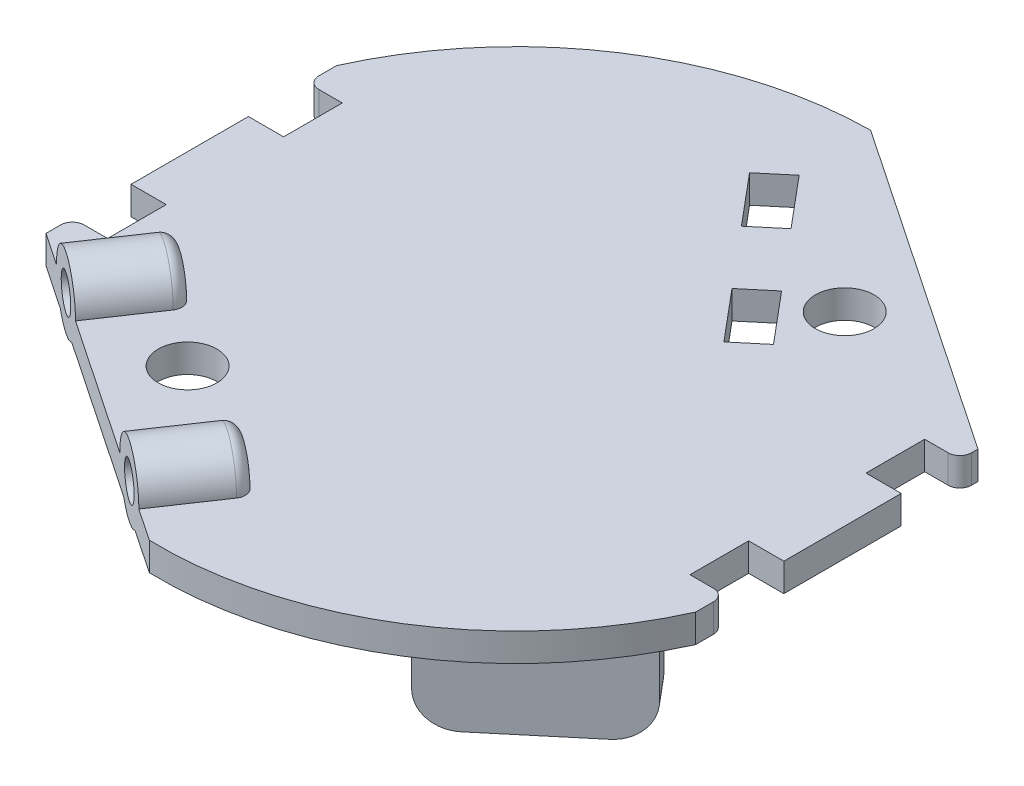
SolidWorks part; units mm, degrees
ref_plane "Alzado" through (0, 0, 0) normal (0, 0, 1) x (1, 0, 0)
ref_plane "Planta" through (0, 0, 0) normal (0, 1, 0) x (1, 0, 0)
ref_plane "Vista lateral" through (0, 0, 0) normal (1, 0, 0) x (0, 0, -1)
sketch "Croquis1" plane through (0, 0, 0) normal (0, 1, 0) x (1, 0, 0)
  circle A0 centre (0, 0) radius 30.5
extrude "Saliente-Extruir1" add sketch "Croquis1" along normal blind 2.4
sketch "Croquis5" plane through (0, 2.4, 0) normal (0, 1, 0) x (1, 0, 0)
  line L0 (0, 0) -> (0, 10)
  line L1 (28.8141, -5) -> (30.0874, -5)
  line L2 (28.8141, 5) -> (30.0874, 5)
  line L3 (-24.8141, 10) -> (-28.8141, 10)
  line L4 (24.8141, -5) -> (24.8141, -10)
  line L5 (-24.8141, -10) -> (-28.8141, -10)
  line L6 (24.8141, -5) -> (28.8141, -5)
  line L7 (24.8141, 5) -> (24.8141, 10)
  line L8 (-24.8141, 5) -> (-28.8141, 5)
  line L9 (-24.8141, 5) -> (-24.8141, 10)
  line L10 (-24.8141, -5) -> (-28.8141, -5)
  line L11 (-24.8141, -5) -> (-24.8141, -10)
  line L12 (24.8141, 5) -> (28.8141, 5)
  line L13 (24.8141, -10) -> (28.8141, -10)
  line L14 (24.8141, 10) -> (28.8141, 10)
  line L15 (-28.8141, 5) -> (-30.0874, 5)
  line L16 (-28.8141, -5) -> (-30.0874, -5)
  circle A1 centre (0, 0) radius 30.5 construction
  arc A2 (-28.8141, 10) -> (-30.0874, 5) centre (0, 0) ccw
  arc A3 (28.8141, 10) -> (28.8141, -10) centre (0, 0) cw
  arc A4 (-30.0874, -5) -> (-28.8141, -10) centre (0, 0) ccw
  arc A5 (30.0874, -5) -> (28.8141, -10) centre (0, 0) cw
  arc A6 (28.8141, 10) -> (30.0874, 5) centre (0, 0) cw
extrude "Cortar-Extruir3" cut sketch "Croquis5" against normal blind 4
sketch "Croquis9" plane through (0, 2.4, 0) normal (0, 1, 0) x (1, 0, 0)
  line L0 (5.6733, 12.6854) -> (8.8872, 8.8552)
  line L2 (7.9714, 14.6138) -> (11.1854, 10.7835)
  line L3 (-24.8141, -5) -> (-24.8141, -10)
  line L4 (-24.8141, -10) -> (-28.8141, -10)
  line L5 (11.1854, 10.7835) -> (8.8872, 8.8552)
  line L7 (7.9714, 14.6138) -> (5.6733, 12.6854)
  line L11 (-2.1205, 21.9737) -> (1.0934, 18.1435)
  line L12 (0.1776, 23.902) -> (3.3916, 20.0718)
  line L13 (-24.8141, 10) -> (-28.8141, 10)
  line L14 (3.3916, 20.0718) -> (1.0934, 18.1435)
  line L15 (0.1776, 23.902) -> (-2.1205, 21.9737)
  arc A1 (28.8141, 10) -> (-28.8141, 10) centre (0, 0) ccw construction
  arc A5 (-28.8141, -10) -> (28.8141, -10) centre (0, 0) ccw construction
  arc A7 (-28.8141, -10) -> (22.3289, -20.7766) centre (0, 0) ccw
  arc A8 (-28.8141, 10) -> (-8.3073, 29.3469) centre (0, 0) cw
extrude "Cortar-Extruir6" cut sketch "Croquis9" against normal blind 10
sketch "Croquis10" plane through (0, 2.4, 0) normal (0, 1, 0) x (1, 0, 0)
  line L0 (0, 0) -> (12, 0)
  line L1 (12, 0) -> (12, 16)
  line L2 (0, 0) -> (-12, 0)
  line L3 (-12, 0) -> (-12, -16)
  circle A0 centre (12, 16) radius 2.5
  circle A1 centre (-12, -16) radius 2.5
extrude "Cortar-Extruir7" cut sketch "Croquis10" against normal blind 10
sketch "Croquis11" plane through (0, 2.4, 0) normal (0, 1, 0) x (1, 0, 0)
  line L0 (27.8141, 5) -> (30.0874, 5)
  line L1 (-27.8141, 5) -> (-27.8141, -5)
  line L2 (-24.8141, -5) -> (-30.0874, -5) construction
  line L3 (27.8141, 10) -> (28.8141, 10)
  line L4 (24.8141, 5) -> (30.0874, 5) construction
  line L5 (27.8141, 5) -> (27.8141, -5)
  line L6 (24.8141, -5) -> (30.0874, -5) construction
  line L7 (27.8141, -5) -> (30.0874, -5)
  line L8 (24.8141, 10) -> (28.8141, 10) construction
  line L9 (27.8141, 10) -> (27.8141, 12.5151)
  line L10 (27.8141, -10) -> (28.8141, -10)
  line L11 (24.8141, -10) -> (28.8141, -10) construction
  line L12 (27.8141, -10) -> (27.8141, -12.5151)
  line L13 (-28.8141, -10) -> (-27.8141, -10)
  line L14 (-24.8141, 10) -> (-28.8141, 10) construction
  line L15 (-27.8141, 10) -> (-27.8141, 12.5151)
  line L16 (-27.8141, -5) -> (-30.0874, -5)
  line L17 (-27.8141, -10) -> (-27.8141, -12.5151)
  line L18 (-27.8141, 10) -> (-28.8141, 10)
  line L19 (-30.0874, 5) -> (-27.8141, 5)
  arc A0 (28.8141, 10) -> (-28.8141, 10) centre (0, 0) ccw construction
  arc A1 (-28.8141, -10) -> (28.8141, -10) centre (0, 0) ccw construction
  arc A2 (28.8141, 10) -> (-28.8141, 10) centre (0, 0) ccw construction
  arc A3 (30.0874, -5) -> (30.0874, 5) centre (0, 0) ccw
  arc A4 (28.8141, -10) -> (27.8141, -12.5151) centre (0, 0) cw
  arc A5 (28.8141, 10) -> (27.8141, 12.5151) centre (0, 0) ccw
  arc A6 (-30.0874, -5) -> (-30.0874, 5) centre (0, 0) cw
  arc A7 (-27.8141, 12.5151) -> (-28.8141, 10) centre (0, 0) ccw
  arc A8 (-28.8141, -10) -> (-27.8141, -12.5151) centre (0, 0) ccw
  arc M11 (28.8141, 10) -> (-28.8141, 10) centre (0, 0) ccw
  line M17 (-24.8141, 5) -> (-30.0874, 5)
  arc M18 (-30.0874, 5) -> (-30.0874, -5) centre (0, 0) ccw
  line M19 (-30.0874, -5) -> (-24.8141, -5)
  arc M21 (-28.8141, -10) -> (28.8141, -10) centre (0, 0) ccw
  line M22 (28.8141, -10) -> (24.8141, -10)
  line M24 (24.8141, -5) -> (30.0874, -5)
  arc M25 (30.0874, -5) -> (30.0874, 5) centre (0, 0) ccw
  line M26 (30.0874, 5) -> (24.8141, 5)
  line M28 (24.8141, 10) -> (28.8141, 10)
  line M54 (-24.8141, -10) -> (-28.8141, -10)
  line M56 (-28.8141, 10) -> (-24.8141, 10)
extrude "Cortar-Extruir8" cut sketch "Croquis11" against normal blind 3 contours L17 M54 M21 | L1 M17 M18 M19 | L15 M56 M11 | L12 M22 M21 | L5 M26 M24 M25 | L9 M28 M11
sketch "Croquis13" plane through (0, 0, 0) normal (0, -1, 0) x (1, 0, 0)
  line L0 (-6.8167, 4.322) -> (-19.6724, -10.9989)
  line L1 (-19.6724, -10.9989) -> (-17.3743, -12.9273)
  line L2 (-17.3743, -12.9273) -> (-4.5186, 2.3936)
  line L3 (-4.5186, 2.3936) -> (-6.8167, 4.322)
  line L4 (21.5273, 8.9312) -> (23.4556, 11.2293)
  line L5 (23.4556, 11.2293) -> (11.965, 20.8711)
  line L6 (11.965, 20.8711) -> (10.0366, 18.573)
  line L7 (10.0366, 18.573) -> (21.5273, 8.9312)
extrude "Saliente-Extruir2" add sketch "Croquis13" along normal blind 10
fillet "Redondeo1" radius 3 4 edges at (11.0008, -10, 19.7221) (22.4915, -10, 10.0802) (-5.6676, -10, 3.3578) (-18.5234, -10, -11.9631)
fillet "Redondeo2" radius 1 6 edges at (17.7103, 0, 16.0502) (11.0008, 0, 19.7221) (-5.6676, 0, 3.3578) (-13.2446, 0, -3.3385) (22.4915, 0, 10.0802) (-18.5234, 0, -11.9631)
sketch "Croquis14" plane through (0, 2.4, 0) normal (0, 1, 0) x (1, 0, 0)
  line L3 (29.8013, 10.2046) -> (-1.7022, 31.454)
  circle A0 centre (0, 0) radius 31.5
  line M12 (27.8141, 10) -> (27.8141, 12.5151)
  arc M13 (27.8141, 12.5151) -> (-27.8141, 12.5151) centre (0, 0) ccw
extrude "Cortar-Extruir9" cut sketch "Croquis14" against normal blind 3 contours L3 M12 M13
sketch "Croquis15" plane through (0, 2.4, 0) normal (0, 1, 0) x (1, 0, 0)
  line L0 (-0.2859, 30.4987) -> (27.8141, 11.545)
  line L1 (-0.2859, 30.4987) -> (-28.711, -11.6433)
  line L2 (27.8141, 11.545) -> (-0.6111, -30.5969)
  line L3 (-28.711, -11.6433) -> (-0.6111, -30.5969)
  line L4 (-27.8141, -12.5151) -> (-27.8141, -12.2483)
  line L5 (-27.8141, -10) -> (-27.8141, -12.5151) construction
  arc A0 (-0.6111, -30.5969) -> (-27.8141, -12.5151) centre (0.1659, 0.0754) cw
extrude "Cortar-Extruir10" cut sketch "Croquis15" against normal blind 10
sketch "Croquis19" plane through (-14.3756, 0, 21.3127) normal (-0.5592, 0, 0.829) x (0.829, 0, 0.5592)
  line L1 (-16.2097, 2.4) -> (16.4123, 2.4) construction
  circle A0 centre (10.1013, 2.4) radius 3
  circle A1 centre (-9.8987, 2.4) radius 3
extrude "Saliente-Extruir5" add sketch "Croquis19" against normal blind 7
sketch "Croquis20" plane through (-14.3756, 0, 21.3127) normal (-0.5592, 0, 0.829) x (0.829, 0, 0.5592)
  circle A0 centre (10.1013, 2.4) radius 1.5
  circle A1 centre (-9.8987, 2.4) radius 1.5
extrude "Cortar-Extruir12" cut sketch "Croquis20" against normal blind 6
fillet "Redondeo3" radius 1 2 edges at (-2.0869, 5.4, 21.158) (-18.6676, 5.4, 9.9741)
fillet "Redondeo4" radius 1 4 edges at (-27.8141, 1.2, 10) (-27.8141, 1.2, -10) (27.8141, 1.2, -10) (27.8141, 1.2, 10)
sketch "Croquis21" plane through (0, 2.4, 0) normal (0, 1, 0) x (1, 0, 0)
  line L0 (5.6733, 12.6854) -> (7.9714, 14.6138)
  line L1 (5.6733, 12.6854) -> (5.4804, 12.9152)
  line L2 (7.9714, 14.6138) -> (7.7786, 14.8436)
  line L3 (5.4804, 12.9152) -> (7.7786, 14.8436)
  line L4 (3.3916, 20.0718) -> (1.0934, 18.1435)
  line L5 (3.3916, 20.0718) -> (3.5844, 19.842)
  line L6 (1.0934, 18.1435) -> (1.2863, 17.9136)
  line L7 (3.5844, 19.842) -> (1.2863, 17.9136)
  line L8 (0.1776, 23.902) -> (-2.1205, 21.9737)
  line L9 (0.1776, 23.902) -> (-0.0152, 24.1319)
  line L10 (-2.1205, 21.9737) -> (-2.3134, 22.2035)
  line L11 (-0.0152, 24.1319) -> (-2.3134, 22.2035)
  line L12 (8.8872, 8.8552) -> (11.1854, 10.7835)
  line L13 (8.8872, 8.8552) -> (9.0801, 8.6254)
  line L14 (11.1854, 10.7835) -> (11.3782, 10.5537)
  line L15 (9.0801, 8.6254) -> (11.3782, 10.5537)
extrude "Cortar-Extruir13" cut sketch "Croquis21" against normal blind 3
